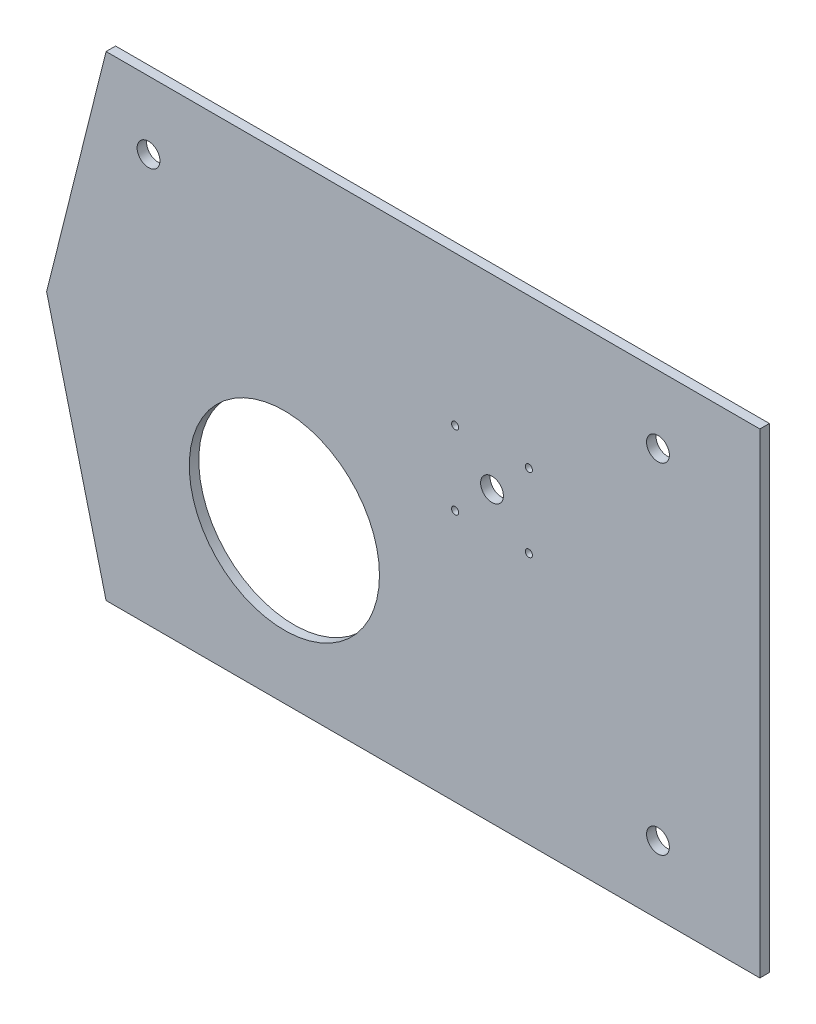
SolidWorks part; units mm, degrees
ref_plane "Front Plane" through (0, 0, 0) normal (0, 0, 1) x (1, 0, 0)
ref_plane "Top Plane" through (0, 0, 0) normal (0, 1, 0) x (1, 0, 0)
ref_plane "Right Plane" through (0, 0, 0) normal (1, 0, 0) x (0, 0, -1)
sketch "Sketch1" plane through (0, 0, 0) normal (0, 0, 1) x (1, 0, 0)
  line L0 (-50, 100) -> (-50, -100) construction
  line L1 (150, -100) -> (-150, -100)
  line L2 (150, -100) -> (150, 100)
  line L3 (150, 100) -> (-150, 100)
  line L4 (-150, -100) -> (-150, 100)
  line L5 (150, -100) -> (-150, 100) construction
  line L6 (150, 100) -> (-150, -100) construction
  line L7 (107.1429, 71.4286) -> (107.1429, -76.2286) construction
  line L8 (-150, 0) -> (150, 0) construction
  line L9 (-107.1429, 71.4286) -> (107.1429, 71.4286) construction
  line L10 (58.4824, 0.502) -> (16.1824, 0.502) construction
  line L11 (58.4824, 0.502) -> (58.4824, 42.802) construction
  line L12 (58.4824, 42.802) -> (16.1824, 42.802) construction
  line L13 (16.1824, 0.502) -> (16.1824, 42.802) construction
  line L14 (58.4824, 0.502) -> (16.1824, 42.802) construction
  line L15 (58.4824, 42.802) -> (16.1824, 0.502) construction
  line L16 (52.8324, 6.152) -> (21.8324, 6.152) construction
  line L17 (52.8324, 6.152) -> (52.8324, 37.152) construction
  line L18 (52.8324, 37.152) -> (21.8324, 37.152) construction
  line L19 (21.8324, 6.152) -> (21.8324, 37.152) construction
  line L20 (52.8324, 6.152) -> (21.8324, 37.152) construction
  line L21 (52.8324, 37.152) -> (21.8324, 6.152) construction
  line L22 (0, 71.4286) -> (107.1429, -71.4286) construction
  line L23 (-107.1429, 71.4286) -> (107.1429, -2.4) construction
  line L24 (-125, 100) -> (-125, -100) construction
  line L25 (-125, -100) -> (-150, 0)
  line L26 (-150, 0) -> (-125, 100)
  circle A0 centre (21.8324, 37.152) radius 1.5
  circle A1 centre (52.8324, 37.152) radius 1.5
  circle A2 centre (52.8324, 6.152) radius 1.5
  circle A3 centre (21.8324, 6.152) radius 1.5
  circle A4 centre (107.1429, 71.4286) radius 4.8
  circle A5 centre (107.1429, -71.4286) radius 4.8
  circle A6 centre (37.3324, 21.652) radius 4.8
  circle A7 centre (-50, -33.3333) radius 40
  circle A8 centre (-107.1429, 71.4286) radius 4.8
  point P0 (0, 0)
  point P6 (-107.1429, 71.4286)
  point P7 (107.1429, 71.4286)
  point P12 (37.3324, 21.652)
  point P27 (107.1429, 71.4286)
  point P28 (107.1429, -71.4286)
  point P36 (-50, -33.3333)
  point P43 (37.3324, 21.652)
  dimension "D5" = 3
  dimension "D6" = 3
  dimension "D7" = 3
  dimension "D8" = 3
  dimension "D13" = 9.6
  dimension "D14" = 9.6
  dimension "D15" = 9.6
  dimension "D16" = 80
  dimension "D17" = 9.6
  dimension "D1" = 300
  dimension "D2" = 200
  dimension "D3" = 42.3
  dimension "D4" = 42.3
  dimension "D9" = 31
  dimension "D10" = 31
  dimension "D11" = 42.8571
  dimension "D12" = 100
  dimension "D18" = 25
sketch "Sketch2" plane through (0, 0, 0) normal (0, 0, 1) x (1, 0, 0)
  line L1 (-108.014, -138.1365) -> (191.986, -138.1365)
  line L2 (-108.014, -138.1365) -> (-108.014, -142.1365)
  line L3 (-108.014, -142.1365) -> (191.986, -142.1365)
  line L4 (191.986, -138.1365) -> (191.986, -142.1365)
  line L5 (41.986, -142.1365) -> (41.986, -138.1365) construction
  line L6 (-108.014, -140.1365) -> (191.986, -140.1365) construction
  point P152 (41.986, -140.1365)
  dimension "D1" = 300
  dimension "D2" = 4
extrude "Boss-Extrude3" add sketch "Sketch1" along normal blind 4 contours L26 L25 L1 L2 L3 A8 A7 A6 A5 A4 A3 A2 A1 A0
equation "\"H\"= 200"
equation "\"L\" = 300"
equation "\"nema_internal\"= 31"
equation "\"nema_external\"= 42.3"
equation "\"bars\"= 9.60"
equation "\"trehead_rods\"= 8"
equation "\"hole_nema\"= 3"
equation "\"D1@Sketch1\"=\"L\""
equation "\"D2@Sketch1\"=\"H\""
equation "\"D3@Sketch1\"=\"nema_external\""
equation "\"D4@Sketch1\"=\"nema_external\""
equation "\"D5@Sketch1\"=\"hole_nema\""
equation "\"D6@Sketch1\"=\"hole_nema\""
equation "\"D7@Sketch1\"=\"hole_nema\""
equation "\"D8@Sketch1\"=\"hole_nema\""
equation "\"D9@Sketch1\"=\"nema_internal\""
equation "\"D10@Sketch1\"=\"nema_internal\""
equation "\"D11@Sketch1\"=\"L\"/7"
equation "\"D12@Sketch1\"=\"L\"/3"
equation "\"D13@Sketch1\"=\"bars\""
equation "\"D14@Sketch1\"=\"bars\""
equation "\"D15@Sketch1\"=\"bars\""
equation "\"ring_dimension_max\" = 80"
equation "\"thik_material\"= 4"
equation "\"D16@Sketch1\"=\"ring_dimension_max\""
equation "\"D17@Sketch1\"=\"bars\""
equation "\"D18@Sketch1\"=\"L\"/12"
equation "\"D1@Sketch2\"=\"L\""
equation "\"D2@Sketch2\"=\"thik_material\""
equation "\"kerf\"= 1"
equation "\"D1@Boss-Extrude3\"=\"thik_material\""
